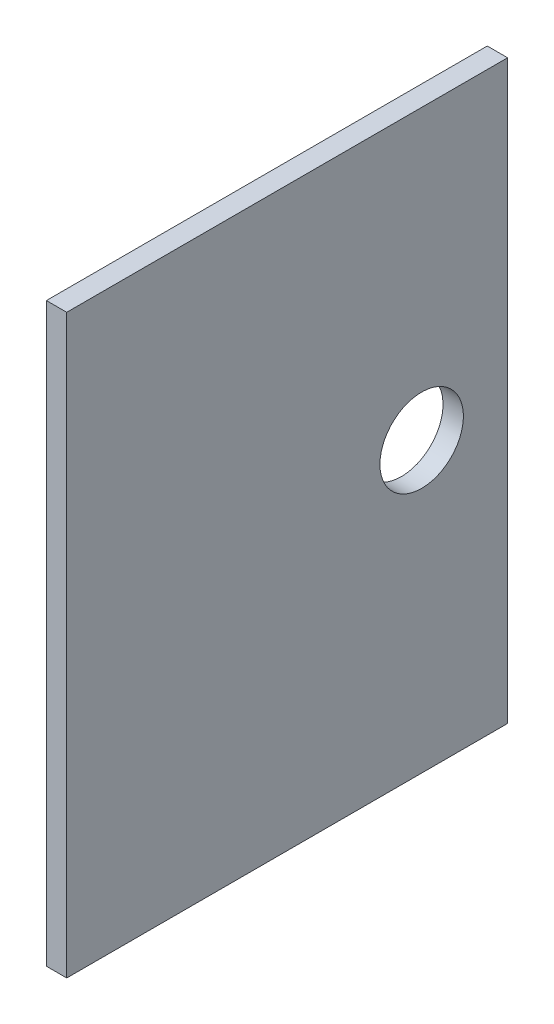
SolidWorks part; units mm, degrees
ref_plane "Front Plane" through (0, 0, 0) normal (0, 0, 1) x (1, 0, 0)
ref_plane "Top Plane" through (0, 0, 0) normal (0, 1, 0) x (1, 0, 0)
ref_plane "Right Plane" through (0, 0, 0) normal (1, 0, 0) x (0, 0, -1)
sketch "Sketch1" plane through (0, 0, 0) normal (1, 0, 0) x (0, 0, -1)
  line L0 (0, 0) -> (50.3611, 0) construction
  line L1 (-82.55, -107.95) -> (82.55, -107.95)
  line L2 (-82.55, -107.95) -> (-82.55, 107.95)
  line L3 (-82.55, 107.95) -> (82.55, 107.95)
  line L4 (82.55, -107.95) -> (82.55, 107.95)
  line L5 (-82.55, -107.95) -> (82.55, 107.95) construction
  line L6 (-82.55, 107.95) -> (82.55, -107.95) construction
  circle A0 centre (50.3611, 0) radius 15.621
  point P0 (0, 0)
  dimension "D1" = 31.242
  dimension "D2" = 165.1
  dimension "D3" = 215.9
extrude "Boss-Extrude1" add sketch "Sketch1" along normal blind 7.62
